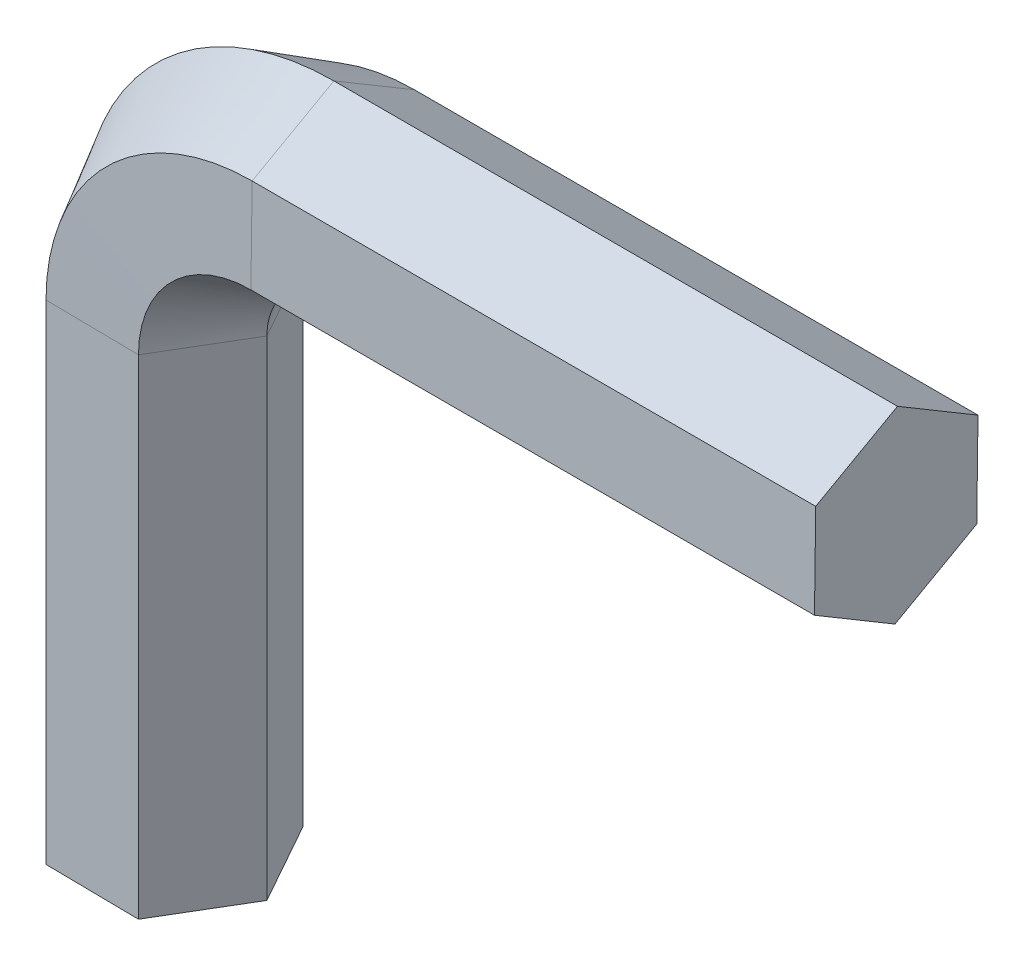
SolidWorks part; units mm, degrees
ref_plane "前视基准面" through (0, 0, 0) normal (0, 0, 1) x (1, 0, 0)
ref_plane "上视基准面" through (0, 0, 0) normal (0, 1, 0) x (1, 0, 0)
ref_plane "右视基准面" through (0, 0, 0) normal (1, 0, 0) x (0, 0, -1)
other "Configuration Table"
sketch "草图2" plane through (0, 0, 0) normal (0, 0, 1) x (1, 0, 0)
  line L0 (0, 0) -> (0, 45.4952)
  line L1 (14.7258, 60.2211) -> (67.177, 60.2211)
  arc A0 (0, 45.4952) -> (14.7258, 60.2211) centre (14.7258, 45.4952) cw
sketch "草图3" plane through (0, 0, 0) normal (0, 1, 0) x (1, 0, 0)
  line L1 (4.2599, -7.6095) -> (8.72, -0.1156)
  line L2 (8.72, -0.1156) -> (4.4601, 7.4939)
  line L3 (4.4601, 7.4939) -> (-4.2599, 7.6095)
  line L4 (-4.2599, 7.6095) -> (-8.72, 0.1156)
  line L5 (-8.72, 0.1156) -> (-4.4601, -7.4939)
  line L6 (-4.4601, -7.4939) -> (4.2599, -7.6095)
  circle A0 centre (0, 0) radius 7.5524 construction
sweep "扫描1" add profiles "草图3" path "草图2"
